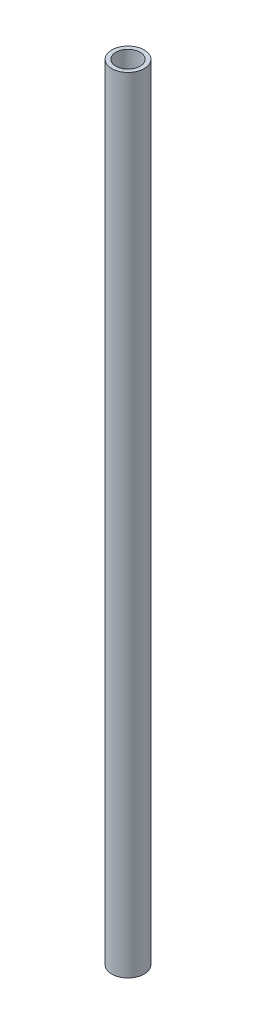
SolidWorks part; units mm, degrees
ref_plane "Front Plane" through (0, 0, 0) normal (0, 0, 1) x (1, 0, 0)
ref_plane "Top Plane" through (0, 0, 0) normal (0, 1, 0) x (1, 0, 0)
ref_plane "Right Plane" through (0, 0, 0) normal (1, 0, 0) x (0, 0, -1)
sketch "Sketch1" plane through (0, 0, 0) normal (0, 1, 0) x (1, 0, 0)
  circle A2 centre (0, 0) radius 2.54
  circle A3 centre (0, 0) radius 1.905
  dimension "D1" = 3.81
  dimension "D2" = 5.08
extrude "Boss-Extrude1" add sketch "Sketch1" along normal blind 122.936
